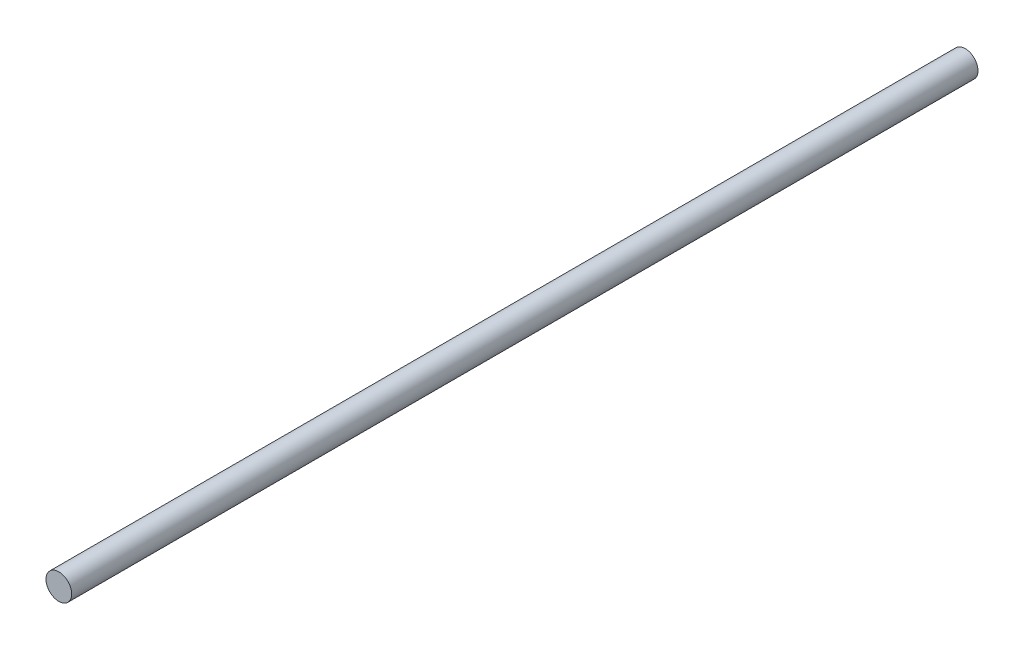
SolidWorks part; units mm, degrees
ref_plane "Front Plane" through (0, 0, 0) normal (0, 0, 1) x (1, 0, 0)
ref_plane "Top Plane" through (0, 0, 0) normal (0, 1, 0) x (1, 0, 0)
ref_plane "Right Plane" through (0, 0, 0) normal (1, 0, 0) x (0, 0, -1)
sketch "Sketch1" plane through (0, 0, 0) normal (0, 0, 1) x (1, 0, 0)
  circle A0 centre (0, 0) radius 1.7
  dimension "D1" = 3.4
extrude "Boss-Extrude1" add sketch "Sketch1" along normal blind 120 contours A0
